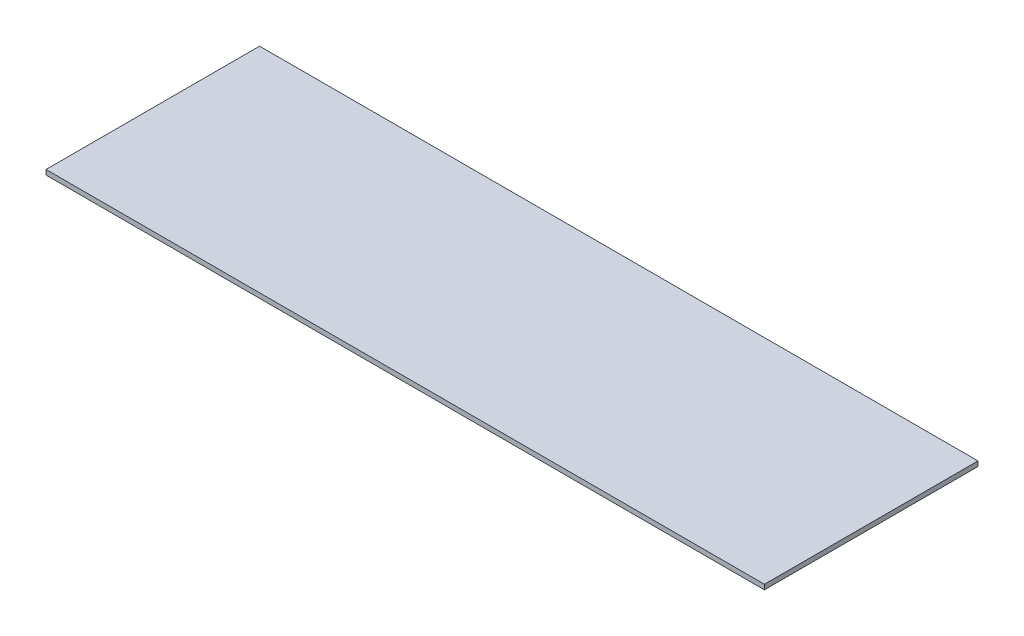
SolidWorks part; units mm, degrees
material "6061 Alloy"
ref_plane "Front Plane" through (0, 0, 0) normal (0, 0, 1) x (1, 0, 0)
ref_plane "Top Plane" through (0, 0, 0) normal (0, 1, 0) x (1, 0, 0)
ref_plane "Right Plane" through (0, 0, 0) normal (1, 0, 0) x (0, 0, -1)
sketch "Sketch1" plane through (0, 0, 0) normal (0, 1, 0) x (1, 0, 0)
  line L1 (-117.475, -34.925) -> (117.475, -34.925)
  line L2 (-117.475, -34.925) -> (-117.475, 34.925)
  line L3 (-117.475, 34.925) -> (117.475, 34.925)
  line L4 (117.475, -34.925) -> (117.475, 34.925)
  line L5 (-117.475, -34.925) -> (117.475, 34.925) construction
  line L6 (-117.475, 34.925) -> (117.475, -34.925) construction
  point P0 (0, 0)
  dimension "D1" = 234.95
  dimension "D2" = 69.85
extrude "Boss-Extrude1" add sketch "Sketch1" along normal blind 1.5875
